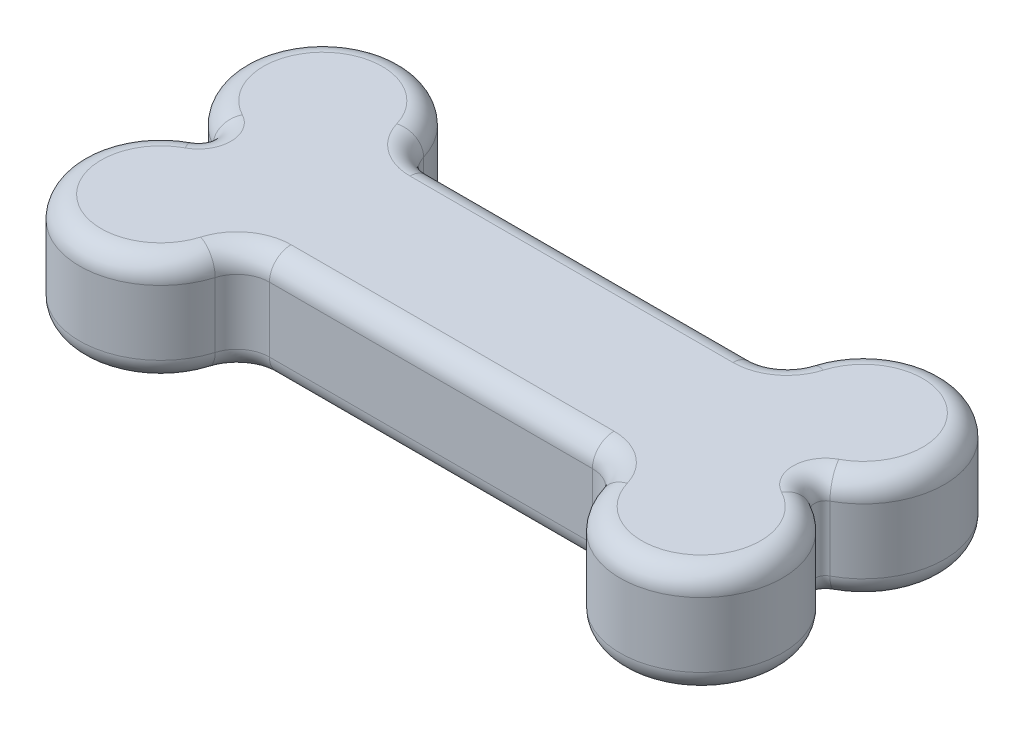
SolidWorks part; units mm, degrees
ref_plane "Front Plane" through (0, 0, 0) normal (0, 0, 1) x (1, 0, 0)
ref_plane "Top Plane" through (0, 0, 0) normal (0, 1, 0) x (1, 0, 0)
ref_plane "Right Plane" through (0, 0, 0) normal (1, 0, 0) x (0, 0, -1)
sketch "Sketch1" plane through (0, 0, 0) normal (0, 1, 0) x (1, 0, 0)
  line L0 (-1000, 0) -> (49000, 0) construction
  line L1 (-17.5, -7.5) -> (17.5, -7.5)
  line L3 (-17.5, 7.5) -> (17.5, 7.5)
  line L5 (-25, -7.5) -> (25, 7.5) construction
  line L6 (-25, 7.5) -> (25, -7.5) construction
  arc A0 (25, 0) -> (17.5, 7.5) centre (25, 7.5) ccw
  arc A1 (17.5, -7.5) -> (25, 0) centre (25, -7.5) ccw
  arc A2 (-17.5, 7.5) -> (-25, 0) centre (-25, 7.5) ccw
  arc A3 (-25, 0) -> (-17.5, -7.5) centre (-25, -7.5) ccw
  point P0 (0, 0)
  point P13 (-25, 0)
  point P14 (25, 0)
  point P15 (25, 0)
  dimension "D1" = 50
  dimension "D2" = 15
extrude "Boss-Extrude1" add sketch "Sketch1" along normal blind 10
fillet "Fillet3" radius 3 4 edges at (-17.5, 5, -7.5) (17.5, 5, -7.5) (17.5, 5, 7.5) (-17.5, 5, 7.5)
fillet "Fillet4" radius 1 2 edges at (-25, 5, 0) (25, 5, 0)
fillet "Fillet5" radius 2 24 edges at (28, 0, 0) (29.7468, 0, -13.3067) (16.7305, 0, -8.0946) (0, 0, -7.5) (-16.7305, 0, -8.0946) (-29.7468, 0, -13.3067) (-28, 0, 0) (-29.7468, 0, 13.3067) (-16.7305, 0, 8.0946) (0, 0, 7.5) (16.7305, 0, 8.0946) (29.7468, 0, 13.3067) (-16.7305, 10, 8.0946) (-29.7468, 10, 13.3067) (-28, 10, 0) (-29.7468, 10, -13.3067) (-16.7305, 10, -8.0946) (0, 10, -7.5) (16.7305, 10, -8.0946) (29.7468, 10, -13.3067) (28, 10, 0) (29.7468, 10, 13.3067) (16.7305, 10, 8.0946) (0, 10, 7.5)
